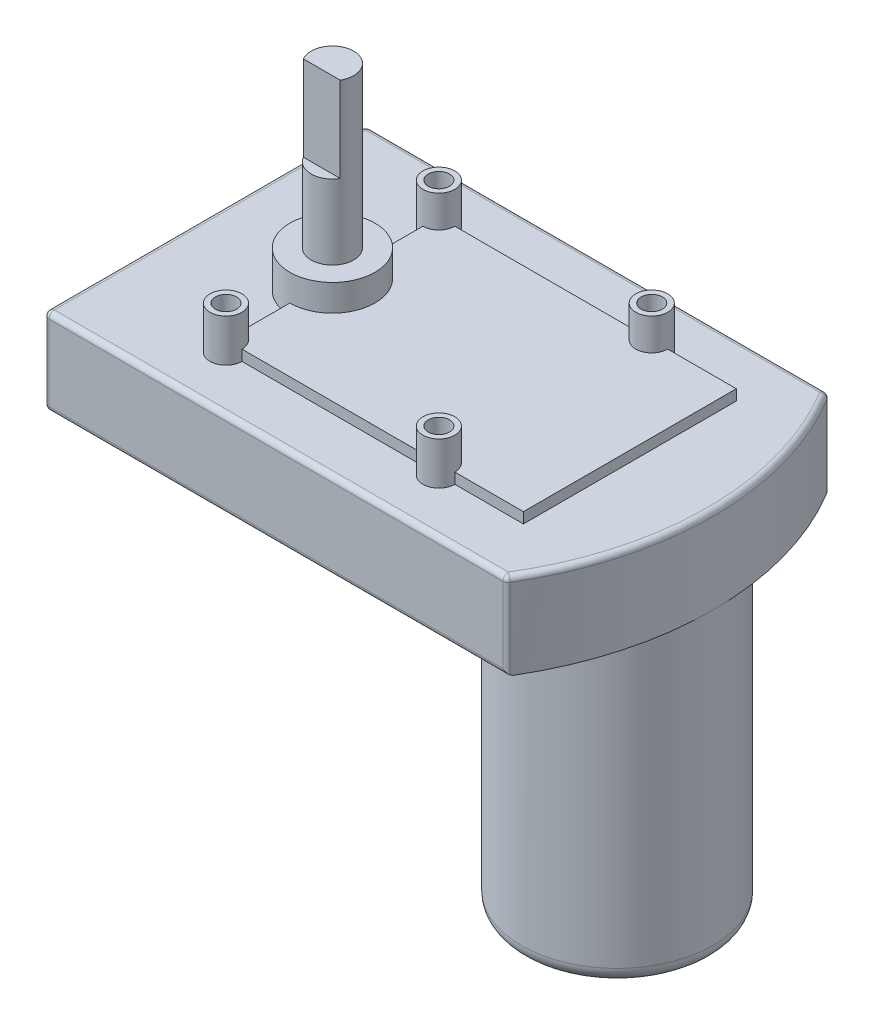
SolidWorks part; units mm, degrees
ref_plane "前视基准面" through (0, 0, 0) normal (0, 0, 1) x (1, 0, 0)
ref_plane "上视基准面" through (0, 0, 0) normal (0, 1, 0) x (1, 0, 0)
ref_plane "右视基准面" through (0, 0, 0) normal (1, 0, 0) x (0, 0, -1)
sketch "草图1" plane through (0, 0, 0) normal (0, 1, 0) x (1, 0, 0)
  line L0 (39.1046, 30.25) -> (39.1046, -30.25) construction
  line L1 (-47.75, 30.25) -> (39.1046, 30.25)
  line L2 (-47.75, 30.25) -> (-47.75, -30.25)
  line L3 (-47.75, -30.25) -> (39.1046, -30.25)
  arc A1 (39.1046, 30.25) -> (39.1046, -30.25) centre (-9.4944, 0) cw
  dimension "D1" = 60.5
  dimension "D3" = 30.25
  dimension "D4" = 47.75
extrude "凸台-拉伸1" add sketch "草图1" along normal blind 16.2
sketch "草图2" plane through (0, 16.2, 0) normal (0, 1, 0) x (1, 0, 0)
  line L0 (-47.75, 30.25) -> (-47.75, -30.25) construction
  line L1 (-47.75, -30.25) -> (39.1046, -30.25) construction
  circle A0 centre (-23.75, -20) radius 3
  circle A1 centre (16.25, -20) radius 3
  circle A2 centre (16.25, 20) radius 3
  circle A3 centre (-23.75, 20) radius 3
  dimension "D1" = 6
  dimension "D2" = 24
  dimension "D3" = 10.25
  dimension "D4" = 2
  dimension "D5" = 2
extrude "凸台-拉伸2" add sketch "草图2" along normal blind 8
sketch "草图3" plane through (0, 24.2, 0) normal (0, 1, 0) x (1, 0, 0)
  circle A0 centre (-23.75, -20) radius 2
  circle A1 centre (16.25, -20) radius 2
  circle A2 centre (16.25, 20) radius 2
  circle A3 centre (-23.75, 20) radius 2
  dimension "D1" = 4
  dimension "D2" = 2
  dimension "D3" = 2
extrude "切除-拉伸1" cut sketch "草图3" against normal blind 8
sketch "草图4" plane through (0, 16.2, 0) normal (0, 1, 0) x (1, 0, 0)
  circle A0 centre (-23.75, 0) radius 8
  dimension "D1" = 16
extrude "凸台-拉伸3" add sketch "草图4" along normal blind 7
sketch "草图5" plane through (0, 23.2, 0) normal (0, 1, 0) x (1, 0, 0)
  circle A0 centre (-23.75, 0) radius 4
  dimension "D1" = 8
extrude "凸台-拉伸4" add sketch "草图5" along normal blind 30
sketch "草图6" plane through (0, 53.2, 0) normal (0, 1, 0) x (1, 0, 0)
  line L7 (-27.2141, -2) -> (-20.2859, -2)
  circle A4 centre (-23.75, 0) radius 4 construction
  arc A6 (-20.2859, -2) -> (-27.2141, -2) centre (-23.75, 0) cw
extrude "切除-拉伸2" cut sketch "草图6" against normal blind 16
sketch "草图7" plane through (0, 16.2, 0) normal (0, 1, 0) x (1, 0, 0)
  line L1 (-23.75, -20) -> (16.25, -20)
  line L2 (-23.75, -20) -> (-23.75, 20)
  line L3 (-23.75, 20) -> (16.25, 20)
  line L5 (32.1396, 20) -> (16.25, 20)
  line L6 (32.1396, 20) -> (32.1396, -20)
  line L7 (32.1396, -20) -> (16.25, -20)
extrude "凸台-拉伸5" add sketch "草图7" along normal blind 2
sketch "草图9" plane through (0, 0, 0) normal (0, -1, 0) x (1, 0, 0)
  line L0 (-47.75, -30.25) -> (-47.75, 30.25) construction
  circle A0 centre (29.75, 0) radius 18
  dimension "D1" = 36
  dimension "D2" = 77.5
extrude "凸台-拉伸6" add sketch "草图9" along normal blind 57.6
fillet "圆角1" radius 3 1 edges at (29.75, -57.6, -18)
fillet "圆角2" radius 1 11 edges at (-4.3227, 16.2, 30.25) (39.1046, 8.1, 30.25) (-4.3227, 0, 30.25) (47.75, 16.2, 0) (-4.3227, 16.2, -30.25) (-4.3227, 0, -30.25) (-47.75, 16.2, 0) (-47.75, 0, 0) (-47.75, 8.1, 30.25) (-47.75, 8.1, -30.25) (39.1046, 8.1, -30.25)
